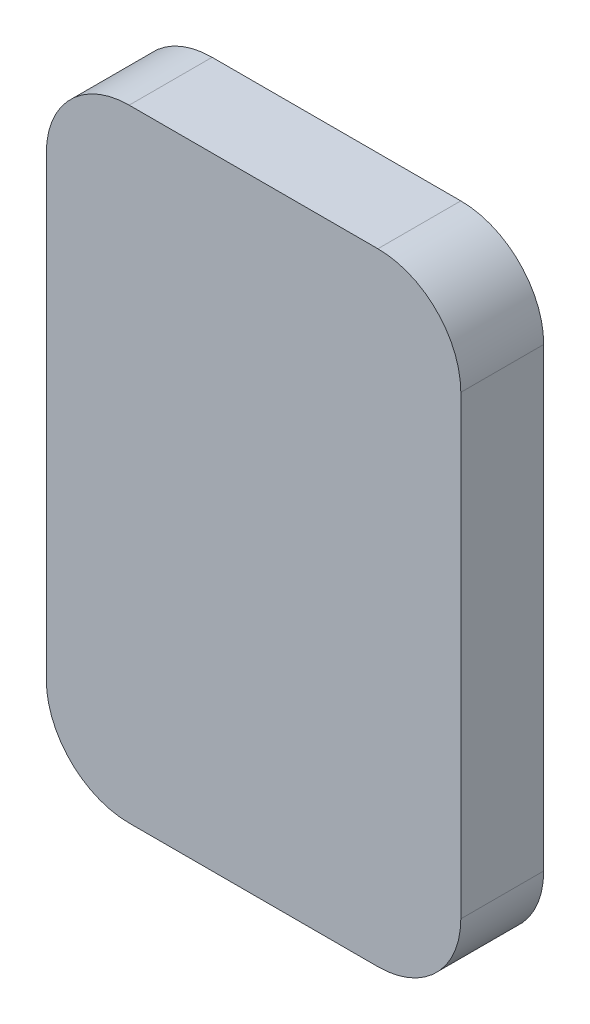
SolidWorks part; units mm, degrees
ref_plane "Front Plane" through (0, 0, 0) normal (0, 0, 1) x (1, 0, 0)
ref_plane "Top Plane" through (0, 0, 0) normal (0, 1, 0) x (1, 0, 0)
ref_plane "Right Plane" through (0, 0, 0) normal (1, 0, 0) x (0, 0, -1)
sketch "Sketch2" plane through (0, 0, 0) normal (0, 1, 0) x (1, 0, 0)
  line L10 (-10.8002, -1.2513) -> (-0.8002, -1.2513)
  line L11 (-10.8002, -1.2513) -> (-10.8002, -3.2513)
  line L12 (-10.8002, -3.2513) -> (-0.8002, -3.2513)
  line L13 (-0.8002, -1.2513) -> (-0.8002, -3.2513)
  line L14 (-10.8002, -1.2513) -> (-0.8002, -3.2513) construction
  line L15 (-10.8002, -3.2513) -> (-0.8002, -1.2513) construction
  point P9 (-5.8002, -2.2513)
  dimension "D4" = 10
  dimension "D5" = 2
extrude "Boss-Extrude1" add sketch "Sketch2" along normal blind 15
ref_plane "Plane1" through (0, 7.5, 0) normal (0, -1, 0) x (-1, 0, 0)
sketch "Sketch3" plane through (0, 7.5, 0) normal (0, -1, 0) x (-1, 0, 0)
  line L0 (4.8002, -1.4379) -> (4.8002, -0.7851)
  line L7 (6.8002, -1.4379) -> (6.8002, -0.7851)
  line L8 (4.4002, 0.4149) -> (4.8002, -0.7851)
  line L9 (4.4002, 1.7987) -> (7.2002, 1.7987)
  line L10 (4.8002, -1.4379) -> (6.8002, -1.4379)
  line L14 (7.2002, 0.4149) -> (7.2002, 1.7987)
  line L16 (4.4002, 0.4149) -> (4.4002, 1.7987)
  line L18 (7.2002, 0.4149) -> (6.8002, -0.7851)
extrude "Boss-Extrude2" add sketch "Sketch3" along normal blind 4.9
fillet "Fillet1" radius 2 4 edges at (-0.8002, 0, 2.2513) (-10.8002, 0, 2.2513) (-10.8002, 15, 2.2513) (-0.8002, 15, 2.2513)
fillet "Fillet2" radius 1 1 edges at (-5.8002, 2.6, 1.2513)
